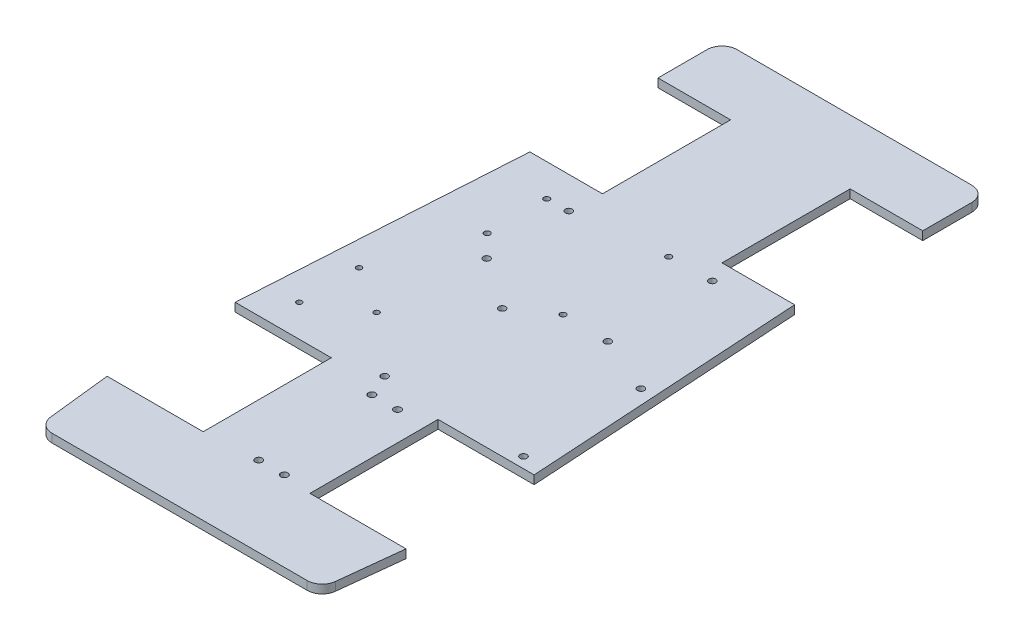
SolidWorks part; units mm, degrees
material "Pine"
ref_plane "Front Plane" through (0, 0, 0) normal (0, 0, 1) x (1, 0, 0)
ref_plane "Top Plane" through (0, 0, 0) normal (0, 1, 0) x (1, 0, 0)
ref_plane "Right Plane" through (0, 0, 0) normal (1, 0, 0) x (0, 0, -1)
sketch "grondplaat groene golf" plane through (0, 0, 0) normal (0, 1, 0) x (1, 0, 0)
  line L21 (-55, 0) -> (55, 0)
  line L22 (62, -7) -> (62, -30)
  line L23 (62, -30) -> (28, -30)
  line L24 (28, -30) -> (28, -90)
  line L25 (28, -90) -> (62, -90)
  line L26 (62, -90) -> (70, -220)
  line L27 (70, -220) -> (25, -220)
  line L28 (25, -220) -> (25, -280)
  line L29 (25, -280) -> (70, -280)
  line L30 (70, -280) -> (66.6919, -309.773)
  line L31 (59.7347, -316) -> (-59.7347, -316)
  line L32 (0, 0) -> (0, -316) construction
  line L33 (-70, -280) -> (-66.6919, -309.773)
  line L34 (-25, -280) -> (-70, -280)
  line L35 (-25, -220) -> (-25, -280)
  line L36 (-70, -220) -> (-25, -220)
  line L37 (-62, -90) -> (-70, -220)
  line L38 (-28, -90) -> (-62, -90)
  line L39 (-28, -30) -> (-28, -90)
  line L40 (-62, -30) -> (-28, -30)
  line L41 (-62, -7) -> (-62, -30)
  arc A4 (-66.6919, -309.773) -> (-59.7347, -316) centre (-59.7347, -309) ccw
  arc A5 (66.6919, -309.773) -> (59.7347, -316) centre (59.7347, -309) cw
  arc A6 (55, 0) -> (62, -7) centre (55, -7) cw
  arc A7 (-62, -7) -> (-55, 0) centre (-55, -7) cw
  dimension "D22" = 7
  dimension "D14" = 124
  dimension "D15" = 124
  dimension "D16" = 60
  dimension "D17" = 45
  dimension "D18" = 30
  dimension "D19" = 34
  dimension "D20" = 130
  dimension "D21" = 45
  dimension "D23" = 133.3838
  dimension "D24" = 119.4694
  dimension "D25" = 70
  dimension "D26" = 60
extrude "Boss-Extrude1" add sketch "grondplaat groene golf" along normal blind 4
hole_wizard "Ø3.3 (3.3) gaten tandwielkast" positions "Sketch1" profile "Sketch2" hole size "Ø3.3" standard "ISO" end condition through all
sketch "Sketch1" plane through (0, 4, 0) normal (0, 1, 0) x (1, 0, 0)
  line L2 (70, -280) -> (25, -280) construction
  line L3 (25, -280) -> (25, -220) construction
  point P0 (11.5, -278.5)
  point P2 (-0.5, -278.5)
  point P4 (-0.5, -225.5)
  point P6 (11.5, -225.5)
  dimension "D1" = 1.5
  dimension "D2" = 13.5
  dimension "D3" = 25.5
  dimension "D4" = 53
sketch "Sketch2" plane through (11.5, 4, 278.5) normal (1, 0, 0) x (0, 0, 1)
  line L0 (0, 0) -> (0, 4)
  line L1 (0, 4) -> (1.65, 4)
  line L2 (1.65, 4) -> (1.65, 0)
  line L5 (1.65, 0) -> (0, 0)
  line L11 (0, -6.35) -> (0, 107.95) construction
  dimension "Thru Hole Dia." = 3.3
  dimension "Thru Hole Depth" = 4
hole_wizard "Ø2.5 (2.5) batterij houder" positions "Sketch3" profile "Sketch4" hole size "Ø2.5" standard "ISO" end condition through all
sketch "Sketch3" plane through (0, 4, 0) normal (0, 1, 0) x (1, 0, 0)
  line L1 (-70, -220) -> (-25, -220) construction
  line L2 (-25, -220) -> (-25, -280) construction
  point P0 (-55, -205)
  point P2 (-32.8, -191)
  point P4 (-55, -177)
  dimension "D1" = 14
  dimension "D2" = 22.2
  dimension "D3" = 15
  dimension "D4" = 28
  dimension "D5" = 30
sketch "Sketch4" plane through (-55, 4, 205) normal (1, 0, 0) x (0, 0, 1)
  line L0 (0, 0) -> (0, 4)
  line L1 (0, 4) -> (1.25, 4)
  line L2 (1.25, 4) -> (1.25, 0)
  line L5 (1.25, 0) -> (0, 0)
  line L11 (0, -6.35) -> (0, 107.95) construction
  dimension "Thru Hole Dia." = 2.5
  dimension "Thru Hole Depth" = 4
hole_wizard "Ø2.7 (2.7) Arduino gaten D2.7" positions "Sketch5" profile "Sketch6" hole size "Ø2.7" standard "ISO" end condition through all
sketch "Sketch5" plane through (0, 4, 0) normal (0, 1, 0) x (1, 0, 0)
  line L0 (-28, -90) -> (-62, -90) construction
  point P0 (-39, -105.09)
  point P2 (-39, -133)
  point P4 (11.76, -148.23)
  point P6 (13.03, -100.01)
  dimension "D1" = 23
  dimension "D2" = 5.08
  dimension "D3" = 52.03
  dimension "D4" = 27.91
  dimension "D5" = 43
  dimension "D6" = 48.22
  dimension "D7" = 1.27
sketch "Sketch6" plane through (-39, 4, 105.09) normal (1, 0, 0) x (0, 0, 1)
  line L0 (0, 0) -> (0, 4)
  line L1 (0, 4) -> (1.35, 4)
  line L2 (1.35, 4) -> (1.35, 0)
  line L5 (1.35, 0) -> (0, 0)
  line L11 (0, -6.35) -> (0, 107.95) construction
  dimension "Thru Hole Dia." = 2.7
  dimension "Thru Hole Depth" = 4
hole_wizard "Ø3.2 (3.2) Arduino gaten D3.2" positions "Sketch7" profile "Sketch8" hole size "Ø3.2" standard "ISO" end condition through all
sketch "Sketch7" plane through (0, 4, 0) normal (0, 1, 0) x (1, 0, 0)
  circle A0 centre (-39, -105.09) radius 1.35 construction
  circle A1 centre (13.03, -100.01) radius 1.35 construction
  point P0 (-28.9, -104.87)
  point P2 (-28.9, -143.37)
  point P4 (33.1, -99.62)
  point P6 (33.1, -148.62)
  dimension "D5" = 0.39
  dimension "D1" = 0.22
  dimension "D2" = 10.1
  dimension "D3" = 38.5
  dimension "D4" = 62
  dimension "D6" = 49
sketch "Sketch8" plane through (-28.9, 4, 104.87) normal (1, 0, 0) x (0, 0, 1)
  line L0 (0, 0) -> (0, 4)
  line L1 (0, 4) -> (1.6, 4)
  line L2 (1.6, 4) -> (1.6, 0)
  line L5 (1.6, 0) -> (0, 0)
  line L11 (0, -6.35) -> (0, 107.95) construction
  dimension "Thru Hole Dia." = 3.2
  dimension "Thru Hole Depth" = 4
hole_wizard "Ø3.2 (3.2) Breadboard ondersteuningsplaatje" positions "Sketch9" profile "Sketch10" hole size "Ø3.2" standard "ISO" end condition through all
sketch "Sketch9" plane through (0, 4, 0) normal (0, 1, 0) x (1, 0, 0)
  line L1 (60, -160) -> (-5, -160) construction
  line L2 (60, -160) -> (60, -215) construction
  line L3 (60, -215) -> (-5, -215) construction
  line L4 (-5, -160) -> (-5, -215) construction
  line L5 (60, -160) -> (-5, -215) construction
  line L6 (60, -215) -> (-5, -160) construction
  line L8 (25, -220) -> (70, -220) construction
  line L9 (25, -280) -> (25, -220) construction
  point P0 (-5, -160)
  point P2 (60, -160)
  point P4 (-5, -215)
  point P6 (60, -215)
  dimension "D1" = 55
  dimension "D2" = 65
  dimension "D3" = 5
  dimension "D4" = 35
sketch "Sketch10" plane through (-5, 4, 160) normal (1, 0, 0) x (0, 0, 1)
  line L0 (0, 0) -> (0, 4)
  line L1 (0, 4) -> (1.6, 4)
  line L2 (1.6, 4) -> (1.6, 0)
  line L5 (1.6, 0) -> (0, 0)
  line L11 (0, -6.35) -> (0, 107.95) construction
  dimension "Thru Hole Dia." = 3.2
  dimension "Thru Hole Depth" = 4
